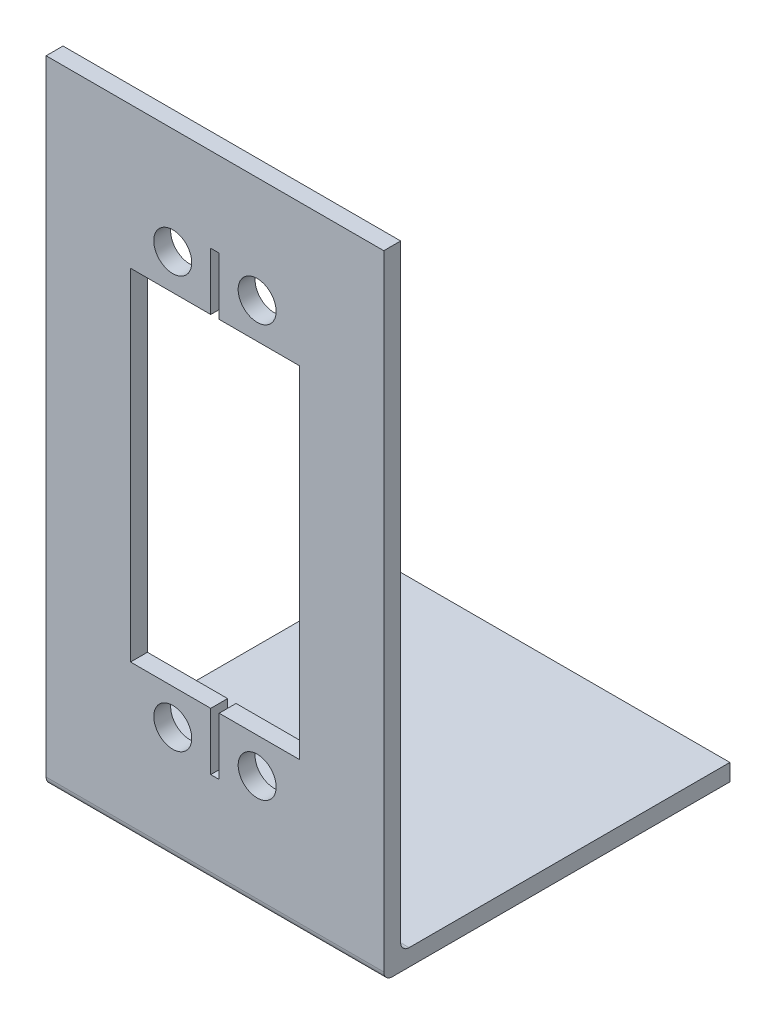
SolidWorks part; units mm, degrees
ref_plane "Front Plane" through (0, 0, 0) normal (0, 0, 1) x (1, 0, 0)
ref_plane "Top Plane" through (0, 0, 0) normal (0, 1, 0) x (1, 0, 0)
ref_plane "Right Plane" through (0, 0, 0) normal (1, 0, 0) x (0, 0, -1)
sketch "Sketch1" plane through (0, 0, 0) normal (0, 1, 0) x (1, 0, 0)
  line L1 (0, 0) -> (40, 0)
  line L2 (0, 0) -> (0, 40)
  line L3 (0, 40) -> (40, 40)
  line L4 (40, 0) -> (40, 40)
  dimension "D1" = 40
  dimension "D2" = 40
extrude "Boss-Extrude1" add sketch "Sketch1" along normal blind 2
sketch "Sketch2" plane through (0, 2, 0) normal (0, 1, 0) x (1, 0, 0)
  line L0 (40, 0) -> (40, 40) construction
  line L1 (0, 0) -> (40, 0)
  line L2 (0, 0) -> (0, 1)
  line L3 (0, 1) -> (40, 1)
  line L4 (40, 0) -> (40, 1)
  line L6 (0, 0) -> (40, 0)
  line L7 (0, 0) -> (0, -1)
  line L8 (0, -1) -> (40, -1)
  line L9 (40, 0) -> (40, -1)
  line M1 (0, 40) -> (0, 0)
  line M2 (0, 0) -> (40, 0)
  line M3 (40, 0) -> (40, 40)
  dimension "D1" = 1
  dimension "D2" = 1
extrude "Boss-Extrude2" add sketch "Sketch2" along normal blind 73 and the other way blind 2 contours L3 M1 M2 M3 | L9 L7 L8 M2
fillet "Fillet1" radius 1 2 edges at (20, 0, 1) (20, 2, -1)
sketch "Sketch4" plane through (0, 0, 1) normal (0, 0, 1) x (1, 0, 0)
  line L0 (20, 75) -> (20, 65)
  line L1 (0, 75) -> (40, 75) construction
  line L3 (20, 65) -> (20.5, 65)
  line L4 (20, 65) -> (20, 58.2)
  line L5 (20, 58.2) -> (20.5, 58.2)
  line L6 (20.5, 65) -> (20.5, 58.2)
  line L7 (20, 65) -> (19.5, 65)
  line L8 (20, 65) -> (20, 58.2)
  line L9 (20, 58.2) -> (19.5, 58.2)
  line L10 (19.5, 65) -> (19.5, 58.2)
  line L11 (20, 58.2) -> (30, 58.2)
  line L12 (20, 58.2) -> (20, 17.8)
  line L13 (20, 17.8) -> (30, 17.8)
  line L14 (30, 58.2) -> (30, 17.8)
  line L15 (20, 58.2) -> (10, 58.2)
  line L16 (20, 58.2) -> (20, 17.8)
  line L17 (20, 17.8) -> (10, 17.8)
  line L18 (10, 58.2) -> (10, 17.8)
  line L19 (20, 17.8) -> (20.5, 17.8)
  line L20 (20, 17.8) -> (20, 11)
  line L21 (20, 11) -> (20.5, 11)
  line L22 (20.5, 17.8) -> (20.5, 11)
  line L23 (20, 17.8) -> (19.5, 17.8)
  line L24 (20, 17.8) -> (20, 11)
  line L25 (20, 11) -> (19.5, 11)
  line L26 (19.5, 17.8) -> (19.5, 11)
  circle A0 centre (15, 62.4) radius 2.25
  circle A1 centre (25, 62.4) radius 2.25
  circle A2 centre (25, 13.6) radius 2.25
  circle A3 centre (15, 13.6) radius 2.25
  dimension "D8" = 4.5
  dimension "D9" = 4.2
  dimension "D10" = 4.5
  dimension "D11" = 4.2
  dimension "D15" = 4.2
  dimension "D1" = 10
  dimension "D2" = 0.5
  dimension "D3" = 0.5
  dimension "D4" = 6.8
  dimension "D5" = 40.4
  dimension "D6" = 10
  dimension "D7" = 10
  dimension "D12" = 0.5
  dimension "D13" = 0.5
  dimension "D14" = 6.8
  dimension "D16" = 4.5
  dimension "D17" = 4.5
  dimension "D18" = 4.2
extrude "Cut-Extrude1" cut sketch "Sketch4" against normal blind 49 contours A0 | L7 L10 L9 L4 | L6 L3 L4 L5 | A1 | L14 L11 L5 L12 L13 | L15 L18 L17 L12 L9 | L17 L26 L25 L20 | A3 | L22 L13 L20 L21 | A2
sketch "Sketch5" plane through (0, 2, 0) normal (0, 1, 0) x (1, 0, 0)
  line L0 (40, 2) -> (40, 40) construction
  line L1 (40, 40) -> (0, 40) construction
  circle A0 centre (20, 15) radius 1.5
  dimension "D1" = 20
  dimension "D2" = 25
hole_wizard "M3 Tapped Hole1" positions "Sketch6" profile "Sketch7" tap size "M3" standard "ISO" end condition through all
sketch "Sketch6" plane through (0, 2, 0) normal (0, 1, 0) x (1, 0, 0)
  point P0 (20, 15)
sketch "Sketch7" plane through (20, 2, -15) normal (1, 0, 0) x (0, 0, 1)
  line L0 (0, 0) -> (0, 2)
  line L1 (0, 2) -> (1.25, 2)
  line L2 (1.25, 2) -> (1.25, 0.275)
  line L3 (1.25, 0.275) -> (1.525, 0)
  line L5 (1.525, 0) -> (0, 0)
  line L6 (-1.25, 0.275) -> (-1.525, 0) construction
  line L11 (0, -6.35) -> (0, 107.95) construction
  dimension "Thru Tap Drill Dia." = 2.5
  dimension "Thru Tap Drill Depth" = 2
  dimension "Near C'Sink Dia." = 3.05
  dimension "Near C'Sink Angle" = 90
cosmetic thread "Hole Thread1" parameters "D2"=3
